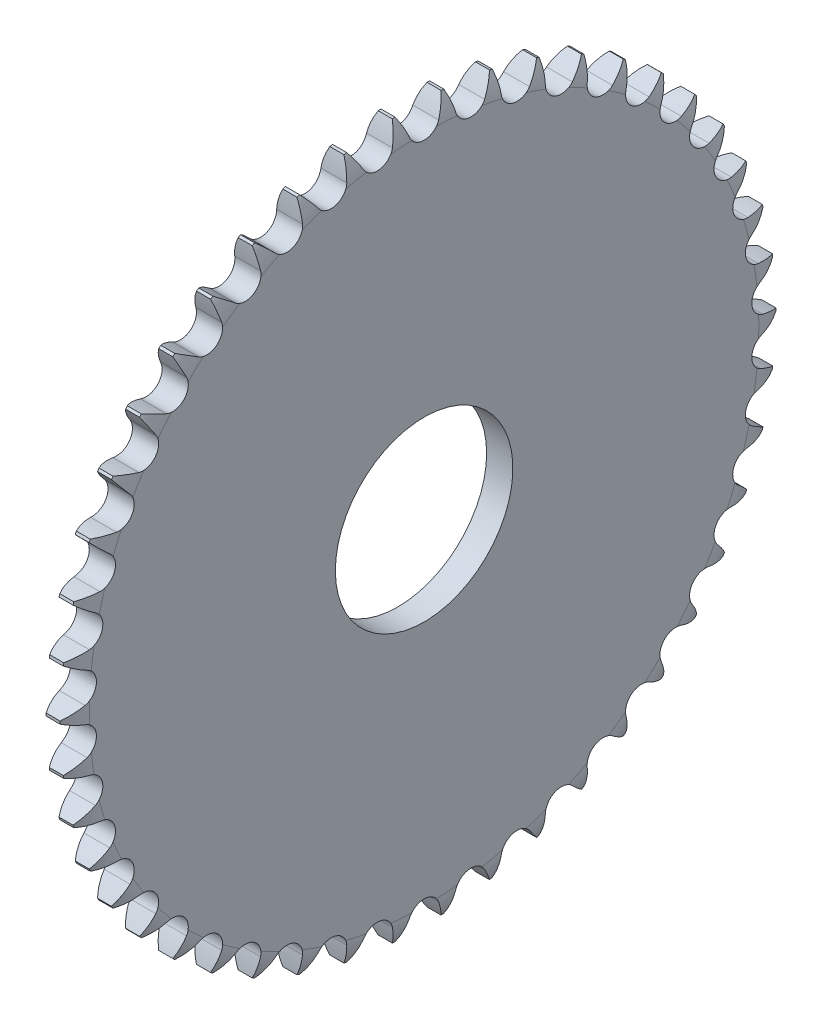
SolidWorks part; units mm, degrees
ref_plane "Plane1" through (0, 0, 0) normal (0, 0, 1) x (1, 0, 0)
ref_plane "Plane2" through (0, 0, 0) normal (0, 1, 0) x (1, 0, 0)
ref_plane "Plane3" through (0, 0, 0) normal (1, 0, 0) x (0, 0, -1)
sketch "Clipboard" plane through (0, 0, 0) normal (0, 1, 0) x (1, 0, 0)
  line L0 (0, 0) -> (6.6166, -6.8517)
  line L1 (-15, 0) -> (100, 0) construction
  line L2 (0, 0) -> (-0.8203, 0.9272)
  line L3 (0, 0) -> (-8.8973, 3.4006)
  line L4 (0, 0) -> (2.1534, 2.23)
  line L5 (0, 0) -> (-46.8476, -17.4728)
  line L6 (0, 0) -> (-4.4098, -2.9753)
  line L7 (-0.8203, 0.9272) -> (33.2799, 37.4952)
  line L8 (-76.2, 38.1) -> (-72.9, 38.1)
  line L9 (-73.3242, 40.7328) -> (-72.926, 40.7699)
  line L10 (-73.4529, 9.1872) -> (-63.2129, 9.1872)
  circle A0 centre (0, 0) radius 3.175
  circle A1 centre (0, 0) radius 37.5
  circle A2 centre (0, 0) radius 37.5
  dimension "Dr" = 6.35
  dimension "MHD" = 75
  dimension "Hub_dia" = 75
  dimension "Num_teeth" = 46
  dimension "Pitch" = 9.525
  dimension "Width" = 3.1
  dimension "Side_relief" = 1.238
  dimension "Side_radius" = 9.525
  dimension "Overall_len" = 50
  dimension "Show_teeth" = 46
  dimension "Thickness" = 5.3196
  dimension "OAL" = 50.0005
  dimension "T_dim" = 3.3
  dimension "Fillet_rad" = 0.4
  dimension "Face_width" = 5.32
  dimension "Num_strands" = 1
  dimension "Transv_pitch" = 10.24
  dimension "Plate_wid" = 8.26
sketch "BasProSke" plane through (0, 0, 0) normal (0, 1, 0) x (1, 0, 0)
  line L0 (-10, 0) -> (60, 0) construction
  line L1 (0, 0) -> (0, 67.8702)
  line L2 (0, 0) -> (5.3196, 0)
  line L3 (5.3196, 0) -> (5.3196, 67.8702)
  line L4 (4.0816, 72.5661) -> (1.238, 72.5661)
  arc A0 (0, 67.8702) -> (1.238, 72.5661) centre (9.525, 67.8702) cw
  arc A1 (5.3196, 67.8702) -> (4.0816, 72.5661) centre (-4.2054, 67.8702) ccw
  dimension "Thickness" = 5.3196
  dimension "D1" = 9.525
  dimension "G1" = 1.238
  dimension "G2" = 1.238
  dimension "Diameter" = 145.1322
revolve "Base-Revolve" add sketch "BasProSke" angle 360 about L0
sketch "TooCutSke" plane through (0, 0, 0) normal (1, 0, 0) x (0, 0, -1)
  line L0 (0, 69.8197) -> (2.9942, 68.6717) construction
  line L1 (0, 0) -> (0, 107) construction
  line L2 (0, 69.8197) -> (-10, 69.8197) construction
  line L3 (0, 69.8197) -> (-2.9942, 68.6717) construction
  arc A0 (2.9942, 68.6717) -> (4.9319, 72.8995) centre (37.1458, 55.577) cw
  arc A1 (2.9942, 68.6717) -> (-2.9942, 68.6717) centre (0, 69.8197) cw
  arc A2 (-2.9942, 68.6717) -> (-4.9319, 72.8995) centre (-37.1458, 55.577) ccw
  arc A3 (4.9319, 72.8995) -> (-4.9319, 72.8995) centre (0, 0) ccw
  dimension "R1" = 3.2067
  dimension "R2" = 36.576
  dimension "Overcut" = 73.0661
  dimension "Seat_radius" = 69.8197
  dimension "X" = 138.043
extrude "ToothCut" cut sketch "TooCutSke" along normal through all
pattern_circular "TeethCuts" count 46 every 7.826 about axis through (-10, 0, 0) along (1, 0, 0) of "ToothCut"
sketch "HubNeaOneSke" plane through (0, 0, 0) normal (-1, 0, 0) x (0, 0, 1)
  circle A0 centre (0, 0) radius 37.5
  dimension "Diameter" = 75
extrude "HubNearOne" [suppressed] add sketch "HubNeaOneSke" along normal blind 44.6809
fillet "HubNearOneFillet" [suppressed] radius 0.4
sketch "HubNeaBotSke" plane through (0, 0, 0) normal (-1, 0, 0) x (0, 0, 1)
  circle A0 centre (0, 0) radius 37.5
  dimension "Diameter" = 75
extrude "HubNearBoth" [suppressed] add sketch "HubNeaBotSke" along normal blind 22.3405
fillet "HubNearBothFillet" [suppressed] radius 0.4
ref_plane "FarPln" through (5.3196, 0, 0) normal (1, 0, 0) x (0, 0, -1)
sketch "HubFarSke" plane through (5.3196, 0, 0) normal (1, 0, 0) x (0, 0, -1)
  circle A0 centre (0, 0) radius 37.5
  dimension "Diameter" = 75
extrude "HubFar" [suppressed] add sketch "HubFarSke" along normal blind 22.3405
fillet "HubFarFillet" [suppressed] radius 0.4
sketch "BorSke" plane through (0, 0, 0) normal (1, 0, 0) x (0, 0, -1)
  circle A0 centre (0, 0) radius 18
  dimension "Diameter" = 36
extrude "Bore" cut sketch "BorSke" along normal mid plane 100.001
sketch "KeySke" plane through (0, 0, 0) normal (1, 0, 0) x (0, 0, -1)
  line L0 (-5, 0) -> (-5, 21.3)
  line L1 (-5, 21.3) -> (5, 21.3)
  line L2 (5, 21.3) -> (5, 0)
  line L3 (0, 0) -> (0, 34) construction
  line L4 (-5, 0) -> (5, 0)
  dimension "Offset" = 21.3
  dimension "Width" = 10
extrude "Keyway" [suppressed] cut sketch "KeySke" along normal mid plane 100.001
pattern_circular "Keyway2" [suppressed] count 2 every 90 about axis through (-10, 0, 0) along (1, 0, 0)
equation "' \"Pitch@Clipboard\" = 12.7"
equation "' \"Num_strands@Clipboard\" = 1"
equation "' \"Num_teeth@Clipboard\" = 9"
equation "' \"Hub_dia@Clipboard\" = 50"
equation "' \"Overall_len@Clipboard\" = 3"
equation "' \"Diameter@BorSke\" = 12"
equation "' \"T_dim@Clipboard\" = 1"
equation "' \"Width@KeySke\" = 2"
equation "' \"Dr@Clipboard\" = 8.51"
equation "' \"Face_width@Clipboard\" = 7.2"
equation "' \"Side_radius@Clipboard\" = 12.7"
equation "' \"Side_relief@Clipboard\" = 1.27"
equation "' \"Transv_pitch@Clipboard\" = 13.92"
equation "' \"Show_teeth@Clipboard\" = 9"
equation "' \"Fillet_rad@Clipboard\" = 0.6"
equation "' \"Plate_wid@Clipboard\" = 11.8"
equation "\"Num_teeth@Clipboard\" = int( \"Num_teeth@Clipboard\" )"
equation "\"Num_teeth@Clipboard\" = ((sgn( \"Num_teeth@Clipboard\" - 5.0)+1)*( \"Num_teeth@Clipboard\" - 5.0))/2 +5.0"
equation "\"Num_teeth@Clipboard\" = ((sgn( \"Num_teeth@Clipboard\" - 200.0)-1)*( \"Num_teeth@Clipboard\" - 200.0))/-2 +200.0"
equation "\"MHD@Clipboard\" = \"Pitch@Clipboard\" * (1.0 / tan(3.14159265 / \"Num_teeth@Clipboard\" )) - 1.04 * \"Plate_wid@Clipboard\" - 0.76"
equation "\"Thickness@Clipboard\"  = \"Face_width@Clipboard\" + (\"Num_strands@Clipboard\" - 1) * \"Transv_pitch@Clipboard\""
equation "\"OAL@Clipboard\" = \"Thickness@Clipboard\" + 2 * \"Fillet_rad@Clipboard\" + 1"
equation "\"MHD@Clipboard\" = ((sgn( \"MHD@Clipboard\" - \"Hub_dia@Clipboard\" )-1)*( \"MHD@Clipboard\" - \"Hub_dia@Clipboard\" ))/-2+ \"Hub_dia@Clipboard\""
equation "\"OAL@Clipboard\" = ((sgn( \"OAL@Clipboard\" - \"Overall_len@Clipboard\" )+1)*( \"OAL@Clipboard\" - \"Overall_len@Clipboard\" ))/2 + \"Overall_len@Clipboard\" + 0.0005"
equation "\"Num_teeth@TeethCuts\" = int( \"Show_teeth@Clipboard\" ) + 1"
equation "\"Num_teeth@TeethCuts\" = ((sgn( \"Num_teeth@TeethCuts\" - \"Num_teeth@Clipboard\" )-1)*( \"Num_teeth@TeethCuts\" - \"Num_teeth@Clipboard\" ))/-2+ \"Num_teeth@Clipboard\""
equation "\"Num_teeth@TeethCuts\" = ((sgn( \"Num_teeth@TeethCuts\" - 2.0)+1)*( \"Num_teeth@TeethCuts\" - 2.0))/2 +2.0"
equation "\"Angle@TeethCuts\" = 360.0 / \"Num_teeth@Clipboard\""
equation "\"Seat_radius@TooCutSke\" = ( \"Pitch@Clipboard\" / 2.0) / sin(3.14159265 / \"Num_teeth@Clipboard\" ) - \"Dr@Clipboard\" / 2.0 + \"Dr@Clipboard\" * 0.505"
equation "\"R1@TooCutSke\"  = \"Dr@Clipboard\" * 0.505"
equation "\"X@TooCutSke\" = 140.0 - (90.0 / \"Num_teeth@Clipboard\")"
equation "\"R2@TooCutSke\" = 0.12 * \"Dr@Clipboard\" * ( \"Num_teeth@Clipboard\" + 2.0)"
equation "\"Overcut@TooCutSke\" = 0.5 + 0.625 * \"Pitch@Clipboard\" - 0.5 * \"Dr@Clipboard\"  +  \"Pitch@Clipboard\" / 2.0 / sin(3.14159265 / \"Num_teeth@Clipboard\" )"
equation "\"Diameter@BasProSke\" = 2.0 * ( 0.625 * \"Pitch@Clipboard\" - 0.5 * \"Dr@Clipboard\"  +  \"Pitch@Clipboard\" / 2.0 / sin(3.14159265 / \"Num_teeth@Clipboard\" ))"
equation "\"Thickness@BasProSke\"  = \"Thickness@Clipboard\""
equation "\"G1@BasProSke\" =  \"Side_relief@Clipboard\""
equation "\"G2@BasProSke\" =  \"Side_relief@Clipboard\""
equation "\"D1@BasProSke\" =  \"Side_radius@Clipboard\""
equation "\"Diameter@HubNeaOneSke\" = \"MHD@Clipboard\""
equation "\"Length@HubNearOne\" = \"OAL@Clipboard\" - \"Thickness@BasProSke\""
equation "\"Diameter@HubNeaBotSke\" = \"MHD@Clipboard\""
equation "\"Length@HubNearBoth\" = ( \"OAL@Clipboard\" - \"Thickness@BasProSke\" ) / 2.0"
equation "\"D1@HubNearOneFillet\" = \"Fillet_rad@Clipboard\""
equation "\"D1@HubNearBothFillet\" = \"Fillet_rad@Clipboard\""
equation "\"Thickness@FarPln\" = \"Thickness@BasProSke\""
equation "\"Diameter@HubFarSke\" = \"MHD@Clipboard\""
equation "\"Length@HubFar\" = ( \"OAL@Clipboard\" - \"Thickness@BasProSke\" ) / 2.0"
equation "\"D1@HubFarFillet\" = \"Fillet_rad@Clipboard\""
equation "\"D1@Bore\" = \"OAL@Clipboard\" * 2.0"
equation "\"D1@Keyway\" = \"OAL@Clipboard\" * 2.0"
equation "\"Offset@KeySke\" = \"T_dim@Clipboard\" + \"Diameter@BorSke\" / 2.0"
